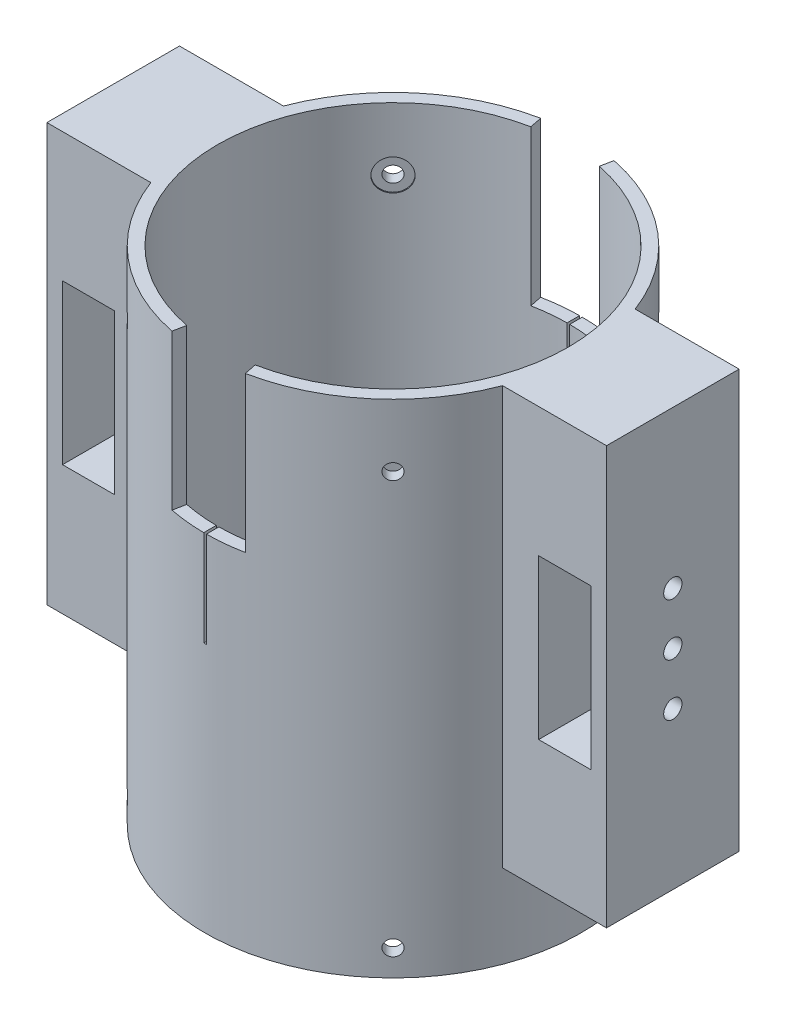
SolidWorks part; units mm, degrees
ref_plane "Front Plane" through (0, 0, 0) normal (0, 0, 1) x (1, 0, 0)
ref_plane "Top Plane" through (0, 0, 0) normal (0, 1, 0) x (1, 0, 0)
ref_plane "Right Plane" through (0, 0, 0) normal (1, 0, 0) x (0, 0, -1)
sketch "Sketch1" plane through (0, 0, 0) normal (0, 1, 0) x (1, 0, 0)
  line L0 (-33.6, 12.7) -> (-33.6, -12.7) construction
  line L1 (-38.3824, 0) -> (22.1691, 0) construction
  line L2 (-33.6855, 12.7) -> (-53.6, 12.7)
  line L11 (-53.6, 12.7) -> (-53.6, -12.7)
  line L12 (-53.6, -12.7) -> (-33.6855, -12.7)
  line L13 (0, 40.1726) -> (0, -46.0062) construction
  line L14 (33.6, 12.7) -> (53.6, 12.7)
  line L15 (53.6, -12.7) -> (33.6, -12.7)
  line L16 (53.6, 12.7) -> (53.6, -12.7)
  circle A2 centre (0, 0) radius 33.6
  arc A3 (-33.6855, -12.7) -> (33.6855, -12.7) centre (0, 0) ccw
  arc A4 (33.6855, 12.7) -> (-33.6855, 12.7) centre (0, 0) ccw
  point P6 (-33.6, 0)
  dimension "D1" = 67.2
  dimension "D2" = 2.4
  dimension "D3" = 25.4
  dimension "D4" = 20
extrude "Boss-Extrude2" add sketch "Sketch1" along normal blind 80
sketch "Sketch6" plane through (0, 80, 0) normal (0, 1, 0) x (1, 0, 0)
  line L0 (0, 43.7956) -> (0, -40.7708) construction
  line L3 (-7.0233, 35.3083) -> (-6.555, 32.9544)
  line L4 (7.0233, 35.3083) -> (6.555, 32.9544)
  line L5 (-7.0233, -35.3083) -> (-6.555, -32.9544)
  line L6 (7.0233, -35.3083) -> (6.555, -32.9544)
  arc A0 (-6.555, -32.9544) -> (6.555, -32.9544) centre (0, 0) ccw
  arc A3 (-7.0233, -35.3083) -> (7.0233, -35.3083) centre (0, 0) ccw
  arc A4 (33.6855, 12.7) -> (-33.6855, 12.7) centre (0, 0) ccw construction
  arc A5 (-33.6855, -12.7) -> (33.6855, -12.7) centre (0, 0) ccw construction
  arc A6 (6.555, 32.9544) -> (-6.555, 32.9544) centre (0, 0) ccw
  arc A7 (7.0233, 35.3083) -> (-7.0233, 35.3083) centre (0, 0) ccw
  point P5 (0, -36)
  point P6 (0, 36)
  dimension "D3" = 67.2
  dimension "D1" = 22.5
extrude "Cut-Extrude3" cut sketch "Sketch6" against normal blind 29.7 and the other way through all
sketch "Sketch7" plane through (0, 0, 0) normal (0, 0, 1) x (1, 0, 0)
  line L0 (0, 0) -> (0, 83.256) construction
  line L1 (-0.25, 50.3) -> (-0.25, 32)
  line L2 (7.0233, 50.3) -> (-7.0233, 50.3) construction
  line L3 (-0.25, 32) -> (0.25, 32)
  line L4 (0.25, 32) -> (0.25, 50.3)
  line L5 (0.25, 50.3) -> (-0.25, 50.3)
  line L6 (-7.0233, 80) -> (-33.6855, 80) construction
  point P7 (0, 50.3)
  dimension "D1" = 0.5
  dimension "D2" = 48
extrude "Cut-Extrude4" cut sketch "Sketch7" against normal through all both and the other way through all
sketch "Sketch9" plane through (0, 0, 12.7) normal (0, 0, 1) x (1, 0, 0)
  line L0 (-45.6, 80) -> (-45.6, 0) construction
  line L1 (-53.6, 80) -> (-33.6855, 80) construction
  line L2 (-53.6, 0) -> (-33.6855, 0) construction
  line L3 (-53.6, 80) -> (-53.6, 0) construction
  line L4 (0, 0) -> (0, 91.1795) construction
  line L5 (-40.6, 24.75) -> (-50.6, 24.75)
  line L6 (-40.6, 24.75) -> (-40.6, 55.25)
  line L7 (-40.6, 55.25) -> (-50.6, 55.25)
  line L8 (-50.6, 24.75) -> (-50.6, 55.25)
  line L9 (-40.6, 24.75) -> (-50.6, 55.25) construction
  line L10 (-40.6, 55.25) -> (-50.6, 24.75) construction
  line L11 (40.6, 55.25) -> (50.6, 55.25)
  line L12 (50.6, 24.75) -> (50.6, 55.25)
  line L13 (40.6, 24.75) -> (50.6, 24.75)
  line L14 (40.6, 24.75) -> (40.6, 55.25)
  point P8 (-45.6, 40)
  dimension "D1" = 8
  dimension "D2" = 10
  dimension "D3" = 30.5
extrude "Cut-Extrude5" cut sketch "Sketch9" against normal through all
sketch "Sketch10" plane through (-53.6, 0, 0) normal (-1, 0, 0) x (0, 0, 1)
  line L0 (0, 0) -> (0, 80) construction
  line L1 (-12.7, 0) -> (12.7, 0) construction
  line L2 (-12.7, 80) -> (12.7, 80) construction
  line L4 (5, 25) -> (-5, 25) construction
  line L5 (5, 25) -> (5, 55) construction
  line L6 (5, 55) -> (-5, 55) construction
  line L7 (-5, 25) -> (-5, 55) construction
  line L8 (5, 25) -> (-5, 55) construction
  line L9 (5, 55) -> (-5, 25) construction
  circle A0 centre (0, 40) radius 1.75
  circle A1 centre (0, 50) radius 1.75
  circle A2 centre (0, 30) radius 1.75
  point P6 (0, 40)
  dimension "D3" = 3.5
  dimension "D1" = 30
  dimension "D2" = 10
  dimension "D4" = 10
  dimension "D5" = 10
extrude "Cut-Extrude6" cut sketch "Sketch10" against normal blind 10
mirror "Mirror1" about plane through (0, 0, 0) normal (1, 0, 0) of "Cut-Extrude6"
ref_plane "Plane2" through (16.6745, 0, 16.6745) normal (0.7071, 0, 0.7071) x (0, 1, 0)
sketch "Sketch11" plane through (16.6745, 0, 16.6745) normal (0.7071, 0, 0.7071) x (0, 1, 0)
  line L0 (0, 0) -> (80, 0) construction
  line L1 (80, -14.839) -> (80, 20.0005) construction
  circle A0 centre (68, 0) radius 3
  dimension "D2" = 6
  dimension "D1" = 12
extrude "Boss-Extrude3" add sketch "Sketch11" along normal up to next
sketch "Sketch12" plane through (16.6745, 0, 16.6745) normal (-0.7071, 0, -0.7071) x (-0.7071, 0, 0.7071)
  circle A0 centre (0, 68) radius 3
  dimension "D1" = 6
extrude "Cut-Extrude7" cut sketch "Sketch12" against normal blind 10.2
sketch "Sketch13" plane through (16.6745, 0, 16.6745) normal (0.7071, 0, 0.7071) x (0, 1, 0)
  line L0 (0, 0) -> (80, 0) construction
  line L1 (80, -14.839) -> (80, 20.0005) construction
  circle A0 centre (68, 0) radius 1.5
  dimension "D2" = 3
  dimension "D1" = 12
extrude "Cut-Extrude9" cut sketch "Sketch13" along normal through all
pattern_circular "CirPattern1" count 4 every 90 about axis through (0, 0, 0) along (0, 1, 0) of "Boss-Extrude3", "Cut-Extrude7", "Cut-Extrude9"
sketch "Sketch14" plane through (0, 0, 0) normal (0, -1, 0) x (1, 0, 0)
  circle A0 centre (0, 0) radius 36
  circle A1 centre (0, 0) radius 33.6
  dimension "D1" = 72
extrude "Boss-Extrude4" add sketch "Sketch14" along normal blind 16
sketch "Sketch15" plane through (0, 0, 0) normal (0, 0, 1) x (1, 0, 0)
  line L0 (0, -16) -> (0, 85.0102) construction
  line L1 (-36, -16) -> (36, -16) construction
ref_plane "Plane3" through (0, 0, 0) normal (0.7071, 0, 0.7071) x (0, 1, 0)
sketch "Sketch17" plane through (0, 0, 0) normal (0.7071, 0, 0.7071) x (0, 1, 0)
  line L0 (-16, 0) -> (79.5812, 0) construction
  line L1 (-16, 0) -> (85.0102, 0) construction
  line L2 (-16, 36) -> (-16, -36) construction
  circle A0 centre (-11, 0) radius 1.5
  dimension "D1" = 3
  dimension "D2" = 5
extrude "Cut-Extrude10" cut sketch "Sketch17" against normal through all
pattern_circular "CirPattern2" count 4 every 90 about axis through (0, 80, 0) along (0, -1, 0) of "Cut-Extrude10"
